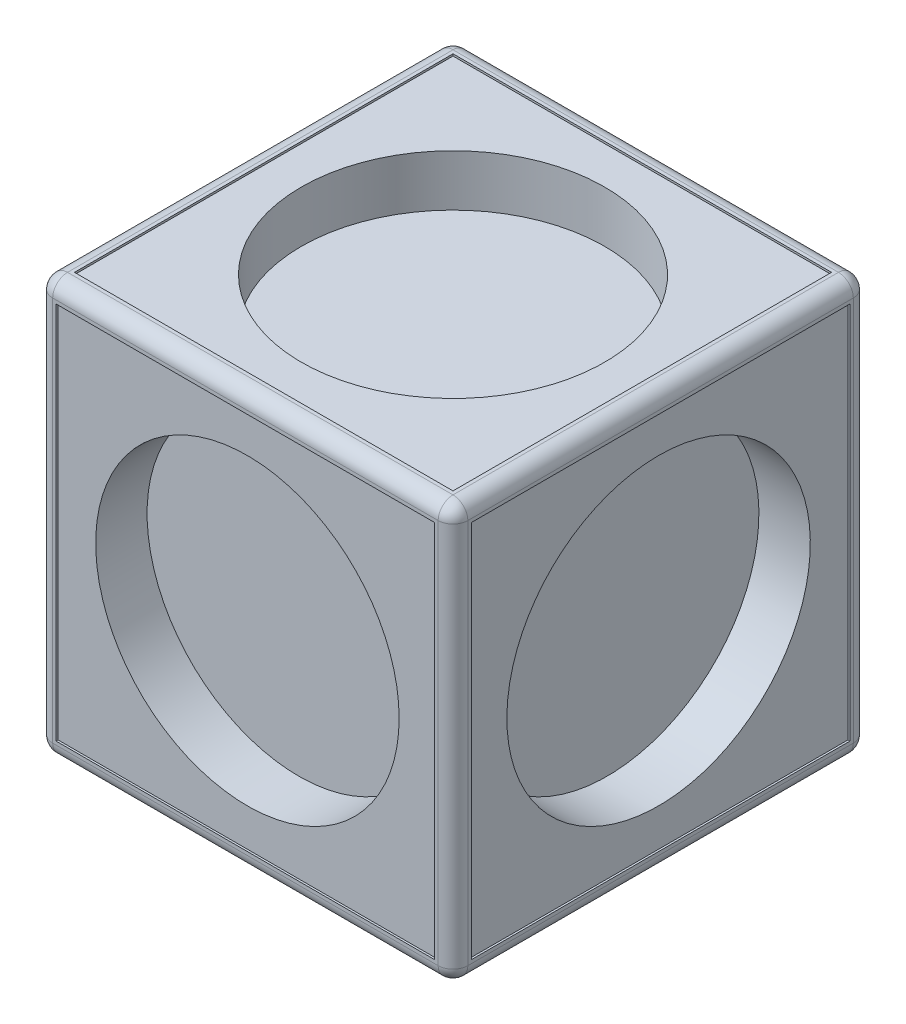
SolidWorks part; units mm, degrees
ref_plane "Front Plane" through (0, 0, 0) normal (0, 0, 1) x (1, 0, 0)
ref_plane "Top Plane" through (0, 0, 0) normal (0, 1, 0) x (1, 0, 0)
ref_plane "Right Plane" through (0, 0, 0) normal (1, 0, 0) x (0, 0, -1)
sketch "Sketch2" plane through (0, 0, 0) normal (0, 0, 1) x (1, 0, 0)
  line L1 (21, 21) -> (-21, 21)
  line L2 (21, 21) -> (21, -21)
  line L3 (21, -21) -> (-21, -21)
  line L4 (-21, 21) -> (-21, -21)
  line L5 (21, 21) -> (-21, -21) construction
  line L6 (21, -21) -> (-21, 21) construction
  point P0 (0, 0)
  dimension "D2" = 42
  dimension "D3" = 42
extrude "Boss-Extrude1" add sketch "Sketch2" along normal blind 42
sketch "Sketch3" plane through (0, 21, 0) normal (0, 1, 0) x (1, 0, 0)
  line L0 (21, -42) -> (-21, -42) construction
  line L1 (-21, -42) -> (21, -42)
  line L2 (-21, -42) -> (-21, 0)
  line L3 (-21, 0) -> (21, 0)
  line L4 (21, -42) -> (21, 0)
  line L5 (-21, -42) -> (-21, 0) construction
  circle A0 centre (0, -21) radius 15.35
  dimension "D1" = 30.7
  dimension "D2" = 21
  dimension "D3" = 21
extrude "Cut-Extrude2" cut sketch "Sketch3" against normal blind 5.4 contours A0
sketch "Sketch4" plane through (0, 21, 0) normal (0, 1, 0) x (1, 0, 0)
  line L1 (-19.15, -40.15) -> (19.15, -40.15)
  line L2 (-19.15, -40.15) -> (-19.15, -1.85)
  line L3 (-19.15, -1.85) -> (19.15, -1.85)
  line L4 (19.15, -40.15) -> (19.15, -1.85)
  line L5 (-19.15, -40.15) -> (19.15, -1.85) construction
  line L6 (-19.15, -1.85) -> (19.15, -40.15) construction
  point P0 (0, -21)
  dimension "D1" = 38.3
  dimension "D2" = 38.3
extrude "Cut-Extrude3" cut sketch "Sketch4" against normal blind 0.2
mirror "Mirror1" about plane through (0, 0, 0) normal (0, 1, 0) of "Cut-Extrude3", "Cut-Extrude2"
sketch "Sketch5" plane through (21, 0, 0) normal (1, 0, 0) x (0, 0, -1)
  line L0 (-42, 21) -> (0, 21) construction
  line L1 (0, -21) -> (0, 21) construction
  circle A0 centre (-21, 0) radius 15.35
  dimension "D1" = 30.7
  dimension "D2" = 21
  dimension "D3" = 21
extrude "Cut-Extrude4" cut sketch "Sketch5" against normal blind 5.4
sketch "Sketch6" plane through (21, 0, 0) normal (1, 0, 0) x (0, 0, -1)
  line L1 (-1.85, 19.15) -> (-40.15, 19.15)
  line L2 (-1.85, 19.15) -> (-1.85, -19.15)
  line L3 (-1.85, -19.15) -> (-40.15, -19.15)
  line L4 (-40.15, 19.15) -> (-40.15, -19.15)
  line L5 (-1.85, 19.15) -> (-40.15, -19.15) construction
  line L6 (-1.85, -19.15) -> (-40.15, 19.15) construction
  point P0 (-21, 0)
  dimension "D1" = 38.3
  dimension "D2" = 38.3
extrude "Cut-Extrude5" cut sketch "Sketch6" against normal blind 0.2
sketch "Sketch7" plane through (0, 0, 42) normal (0, 0, 1) x (1, 0, 0)
  circle A0 centre (0, 0) radius 15.35
  dimension "D1" = 30.7
extrude "Cut-Extrude6" cut sketch "Sketch7" against normal blind 5.4
sketch "Sketch8" plane through (0, 0, 42) normal (0, 0, 1) x (1, 0, 0)
  line L1 (19.15, 19.15) -> (-19.15, 19.15)
  line L2 (19.15, 19.15) -> (19.15, -19.15)
  line L3 (19.15, -19.15) -> (-19.15, -19.15)
  line L4 (-19.15, 19.15) -> (-19.15, -19.15)
  line L5 (19.15, 19.15) -> (-19.15, -19.15) construction
  line L6 (19.15, -19.15) -> (-19.15, 19.15) construction
  point P0 (0, 0)
  dimension "D1" = 38.3
  dimension "D2" = 38.3
extrude "Cut-Extrude7" cut sketch "Sketch8" against normal blind 0.2
mirror "Mirror2" about plane through (0, 0, 0) normal (1, 0, 0) of "Cut-Extrude5", "Cut-Extrude4"
ref_plane "Plane1" through (0, 0, 21) normal (0, 0, -1) x (-1, 0, 0)
mirror "Mirror3" about plane through (0, 0, 21) normal (0, 0, -1) of "Cut-Extrude7", "Cut-Extrude6"
fillet "Fillet1" radius 1.5 12 edges at (21, -21, 21) (0, -21, 0) (-21, -21, 21) (-21, 0, 42) (0, -21, 42) (0, 21, 42) (21, 0, 42) (21, 21, 21) (21, 0, 0) (-21, 0, 0) (0, 21, 0) (-21, 21, 21)
